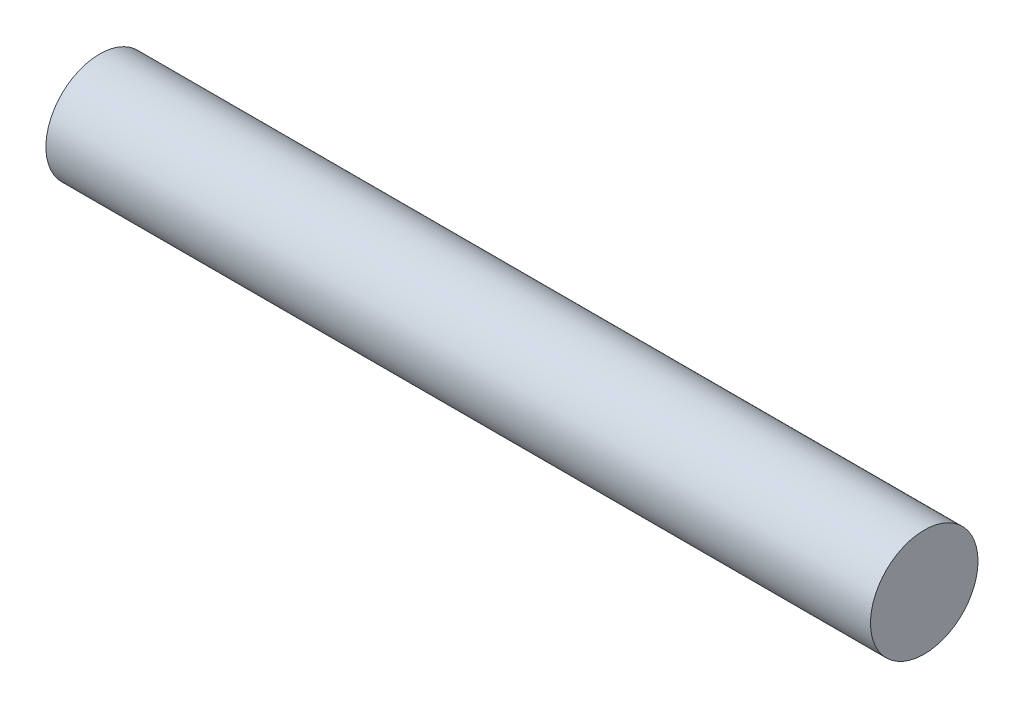
SolidWorks part; units mm, degrees
ref_plane "Front Plane" through (0, 0, 0) normal (0, 0, 1) x (1, 0, 0)
ref_plane "Top Plane" through (0, 0, 0) normal (0, 1, 0) x (1, 0, 0)
ref_plane "Right Plane" through (0, 0, 0) normal (1, 0, 0) x (0, 0, -1)
sketch "Sketch1" plane through (0, 0, 0) normal (1, 0, 0) x (0, 0, -1)
  circle A0 centre (0, 0) radius 8.89
  dimension "D1" = 17.78
extrude "Boss-Extrude1" add sketch "Sketch1" along normal blind 3.2 and the other way blind 133.2
